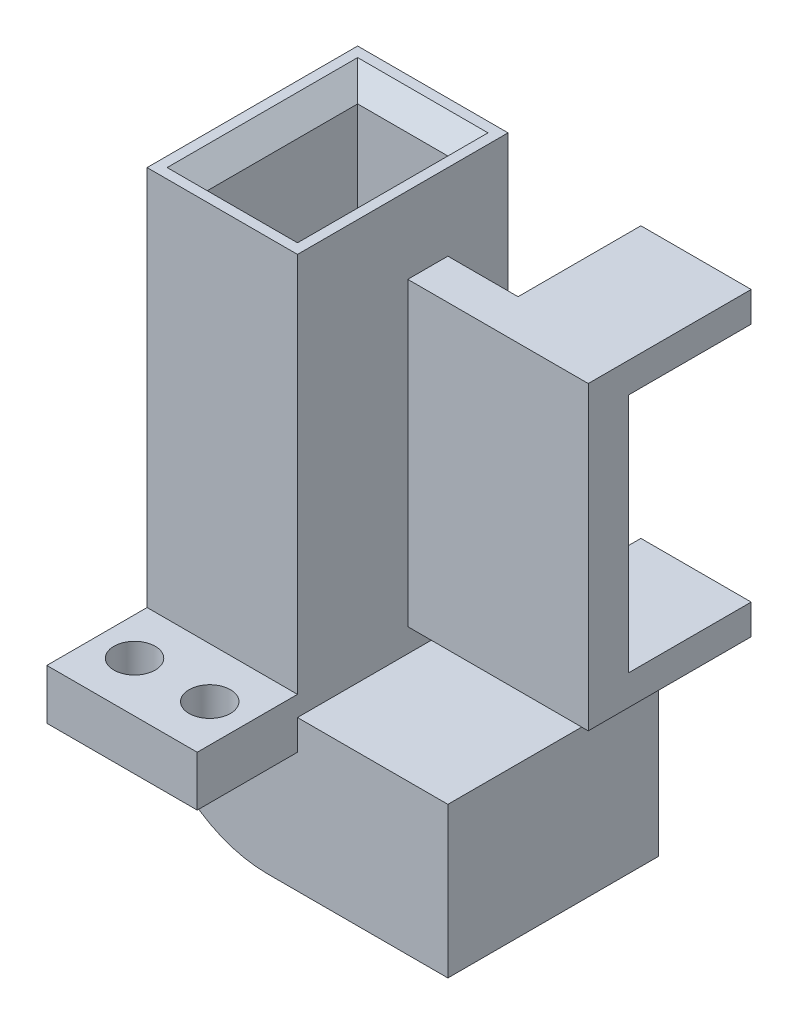
SolidWorks part; units mm, degrees
ref_plane "Front Plane" through (0, 0, 0) normal (0, 0, 1) x (1, 0, 0)
ref_plane "Top Plane" through (0, 0, 0) normal (0, 1, 0) x (1, 0, 0)
ref_plane "Right Plane" through (0, 0, 0) normal (1, 0, 0) x (0, 0, -1)
sketch "Sketch1" plane through (0, 0, 0) normal (0, 0, 1) x (1, 0, 0)
  line L0 (0, 43) -> (0, 0)
  line L1 (0, -9) -> (0, -12)
  line L2 (3, 3) -> (3, 43)
  line L3 (3, 43) -> (0, 43)
  line L4 (-9, 43) -> (-12, 43)
  line L5 (-12, 43) -> (-12, 0)
  line L6 (0, 0) -> (15, 0)
  line L7 (-9, 0) -> (-9, 43)
  line L8 (15, 0) -> (15, -12)
  line L9 (15, -12) -> (18, -12)
  line L10 (18, -12) -> (18, 3)
  line L11 (18, 3) -> (3, 3)
  arc A0 (-9, 0) -> (0, -9) centre (0, 0) ccw
  arc A1 (-12, 0) -> (0, -12) centre (0, 0) ccw
  point P10 (0, 0)
  point P16 (0, 0)
  point P17 (0, 0)
  point P18 (0, 0)
  dimension "D7" = 9
  dimension "D1" = 9
  dimension "D2" = 3
  dimension "D3" = 3
  dimension "D4" = 3
  dimension "D5" = 3
  dimension "D6" = 3
  dimension "D8" = 15
  dimension "D9" = 40
extrude "Boss-Extrude1" add sketch "Sketch1" along normal blind 15
sketch "Sketch2" plane through (0, 0, 0) normal (0, 0, -1) x (-1, 0, 0)
  line L0 (-3, 43) -> (12, 43)
  line L1 (12, 43) -> (12, 0)
  line L2 (0, -12) -> (-18, -12)
  line L3 (-18, -12) -> (-18, 3)
  line L4 (-18, -12) -> (-18, 3) construction
  line L5 (-18, 3) -> (-3, 3) construction
  line L6 (-18, 3) -> (-3, 3)
  line L7 (-3, 3) -> (-3, 43)
  line L8 (0, 28) -> (9, 28)
  line L9 (0, 43) -> (0, 0) construction
  line L10 (9, 0) -> (9, 43) construction
  line L11 (9, 28) -> (9, 3)
  line L12 (9, 3) -> (0, 3)
  line L13 (0, 3) -> (0, 28)
  arc A0 (12, 0) -> (0, -12) centre (0, 0) cw
  dimension "D1" = 25
extrude "Boss-Extrude2" add sketch "Sketch2" along normal blind 3
sketch "Sketch3" plane through (0, 0, 15) normal (0, 0, 1) x (1, 0, 0)
  line L0 (-12, 0) -> (-12, 43)
  line L1 (-12, 43) -> (3, 43)
  line L2 (3, 43) -> (3, 3)
  line L3 (3, 3) -> (18, 3)
  line L4 (18, 3) -> (18, -12)
  line L5 (18, -12) -> (0, -12)
  arc A0 (-12, 0) -> (0, -12) centre (0, 0) ccw
extrude "Boss-Extrude3" add sketch "Sketch3" along normal blind 3
sketch "Sketch4" plane through (0, 0, -3) normal (0, 0, -1) x (-1, 0, 0)
  line L0 (0, 15.5) -> (9, 15.5) construction
  line L1 (0, 28) -> (0, 3) construction
  line L2 (9, 3) -> (9, 28) construction
  line L3 (-3, 43) -> (-3, 3) construction
  line L4 (-3, 24.6973) -> (0, 24.6973)
  line L5 (-3, 24.6973) -> (-3, 9.3)
  line L6 (-3, 9.3) -> (0, 9.3)
  line L7 (0, 24.6973) -> (0, 9.3)
  point P12 (-1.5, 24.6973)
  dimension "D1" = 6.2
  dimension "D2" = 9.1973
extrude "Cut-Extrude1" cut sketch "Sketch4" against normal blind 6
sketch "Sketch5" plane through (3, 0, 0) normal (1, 0, 0) x (0, 0, -1)
  line L1 (-3, 24.6973) -> (3, 24.6973) construction
  line L2 (-3, 32.3473) -> (-3, 8.3473)
  line L4 (-7, 32.3473) -> (-7, 8.3473)
  line L5 (-3, 24.6973) -> (-3, 9.3) construction
  line L6 (-7, 32.3473) -> (-7, 35.3473)
  line L7 (-7, 35.3473) -> (-3, 35.3473)
  line L8 (-3, 35.3473) -> (-3, 32.3473)
  line L9 (-7, 8.3473) -> (-7, 5.3473)
  line L10 (-7, 5.3473) -> (-3, 5.3473)
  line L11 (-3, 5.3473) -> (-3, 8.3473)
  dimension "D1" = 24
  dimension "D2" = 4
  dimension "D3" = 7.65
  dimension "D4" = 3
  dimension "D5" = 3
extrude "Boss-Extrude4" add sketch "Sketch5" along normal blind 18
sketch "Sketch7" plane through (0, 0, 3) normal (0, 0, -1) x (-1, 0, 0)
  line L1 (-21, 35.3473) -> (-10, 35.3473)
  line L2 (-21, 35.3473) -> (-21, 32.3473)
  line L3 (-21, 32.3473) -> (-10, 32.3473)
  line L4 (-10, 35.3473) -> (-10, 32.3473)
  line L6 (-10, 8.3473) -> (-21, 8.3473)
  line L7 (-10, 8.3473) -> (-10, 5.3473)
  line L8 (-10, 5.3473) -> (-21, 5.3473)
  line L9 (-21, 8.3473) -> (-21, 5.3473)
  dimension "D1" = 3
  dimension "D2" = 3
  dimension "D3" = 11
extrude "Boss-Extrude5" add sketch "Sketch7" along normal blind 12.25
chamfer "Chamfer1" distance 2 angle 45 4 edges at (-4.5, 43, 0) (-9, 43, 7.5) (-4.5, 43, 15) (0, 43, 7.5)
sketch "Sketch8" plane through (0, 0, 18) normal (0, 0, 1) x (1, 0, 0)
  line L0 (18, -12) -> (-12, -12) construction
  line L1 (-12, -12) -> (-12, 0) construction
  line L2 (-12, 43) -> (-12, 0) construction
  line L3 (-12, 0) -> (3, 0)
  line L5 (-12, 0) -> (-12, 5)
  line L6 (-12, 5) -> (3, 5)
  line L7 (3, 3) -> (3, 43) construction
  line L8 (3, 5) -> (3, 0)
  dimension "D1" = 12
  dimension "D2" = 5
extrude "Boss-Extrude6" add sketch "Sketch8" along normal blind 10
sketch "Sketch9" plane through (0, 5, 0) normal (0, 1, 0) x (1, 0, 0)
  line L0 (-4.5, -18) -> (-4.5, -28) construction
  line L1 (3, -18) -> (-12, -18) construction
  line L2 (3, -28) -> (-12, -28) construction
  line L3 (-4.5, -23) -> (-12, -23) construction
  line L4 (-12, -28) -> (-12, -18) construction
  circle A0 centre (-8.25, -23) radius 2.0625
  circle A1 centre (-0.75, -23) radius 2.0625
  point P12 (-8.25, -23)
  dimension "D1" = 4.125
extrude "Cut-Extrude2" cut sketch "Sketch9" against normal through all
